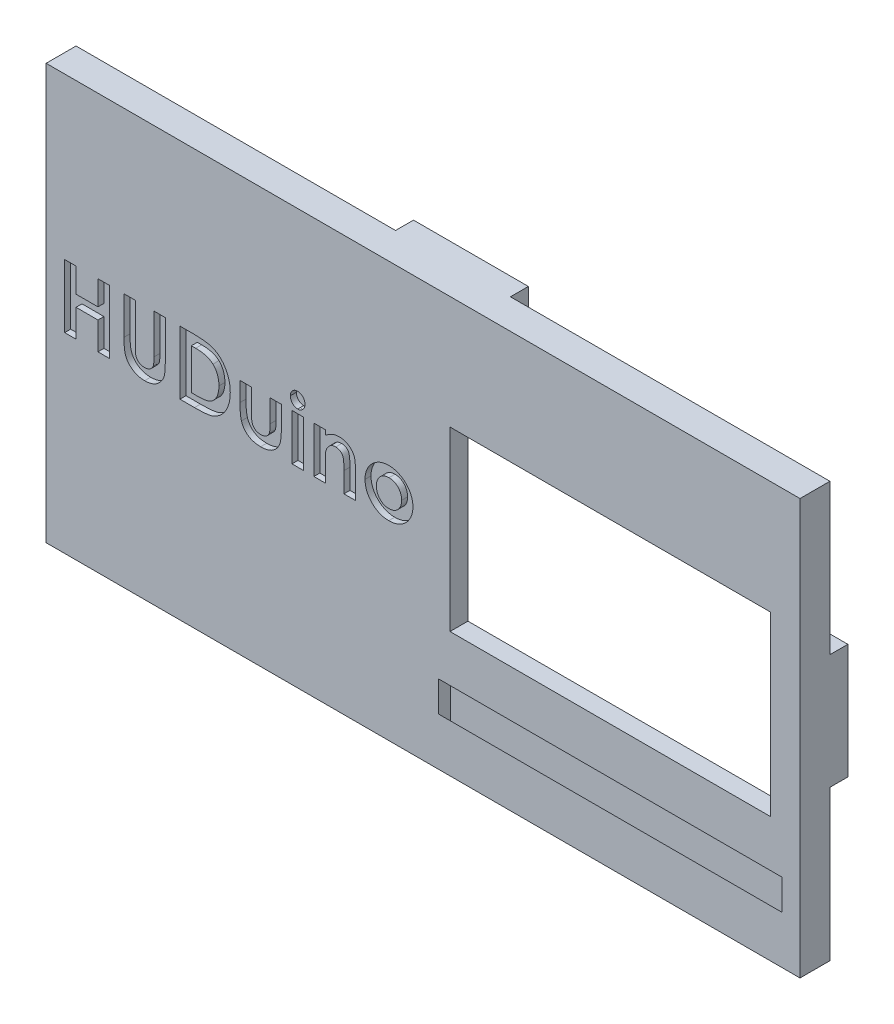
SolidWorks part; units mm, degrees
ref_plane "Alzado" through (0, 0, 0) normal (0, 0, 1) x (1, 0, 0)
ref_plane "Planta" through (0, 0, 0) normal (0, 1, 0) x (1, 0, 0)
ref_plane "Vista lateral" through (0, 0, 0) normal (1, 0, 0) x (0, 0, -1)
sketch "Croquis1" plane through (0, 0, 0) normal (0, 0, 1) x (1, 0, 0)
  line L1 (-29.7943, 14.4088) -> (33.2057, 14.4088)
  line L2 (-29.7943, 14.4088) -> (-29.7943, -20.2912)
  line L3 (-29.7943, -20.2912) -> (33.2057, -20.2912)
  line L4 (33.2057, 14.4088) -> (33.2057, -20.2912)
  dimension "D1" = 63
  dimension "D2" = 34.7
extrude "Saliente-Extruir1" add sketch "Croquis1" along normal blind 1.5
sketch "Croquis3" plane through (0, 0, 0) normal (0, 0, -1) x (-1, 0, 0)
  line L1 (-33.2057, 14.4088) -> (29.7943, 14.4088)
  line L2 (-33.2057, 14.4088) -> (-33.2057, -20.2912)
  line L3 (-33.2057, -20.2912) -> (29.7943, -20.2912)
  line L4 (29.7943, 14.4088) -> (29.7943, -20.2912)
  line L5 (-31.7057, 12.9088) -> (28.2943, 12.9088)
  line L6 (-31.7057, 12.9088) -> (-31.7057, -18.7912)
  line L7 (-31.7057, -18.7912) -> (28.2943, -18.7912)
  line L8 (28.2943, 12.9088) -> (28.2943, -18.7912)
  dimension "D1" = 1.5
  dimension "D2" = 1.5
  dimension "D3" = 1.5
  dimension "D4" = 1.5
extrude "Saliente-Extruir2" add sketch "Croquis3" along normal blind 1
sketch "Croquis4" plane through (0, 0, -1) normal (0, 0, -1) x (-1, 0, 0)
  line L0 (29.7943, 14.4088) -> (-33.2057, 14.4088) construction
  line L1 (-6.5057, 14.4088) -> (3.0943, 14.4088)
  line L2 (-6.5057, 14.4088) -> (-6.5057, 12.9088)
  line L3 (-6.5057, 12.9088) -> (3.0943, 12.9088)
  line L4 (3.0943, 14.4088) -> (3.0943, 12.9088)
  line L5 (28.2943, 12.9088) -> (-31.7057, 12.9088) construction
  line L6 (-33.2057, 14.4088) -> (-33.2057, -20.2912) construction
  line L7 (-33.2057, 1.8588) -> (-31.7057, 1.8588)
  line L8 (-33.2057, 1.8588) -> (-33.2057, -7.7412)
  line L9 (-33.2057, -7.7412) -> (-31.7057, -7.7412)
  line L10 (-31.7057, 1.8588) -> (-31.7057, -7.7412)
  line L11 (-31.7057, 12.9088) -> (-31.7057, -18.7912) construction
  line L17 (29.7943, -20.2912) -> (29.7943, 14.4088) construction
  line L18 (-31.7057, -18.7912) -> (28.2943, -18.7912) construction
  line L19 (3.0943, -18.7912) -> (-6.5057, -18.7912)
  line L20 (3.0943, -18.7912) -> (3.0943, -20.2912)
  line L21 (3.0943, -20.2912) -> (-6.5057, -20.2912)
  line L22 (-6.5057, -18.7912) -> (-6.5057, -20.2912)
  line L23 (-33.2057, -20.2912) -> (29.7943, -20.2912) construction
  line L24 (28.2943, -18.7912) -> (28.2943, 12.9088) construction
  line L25 (28.2943, 1.8588) -> (29.7943, 1.8588)
  line L26 (28.2943, 1.8588) -> (28.2943, -7.7412)
  line L27 (28.2943, -7.7412) -> (29.7943, -7.7412)
  line L28 (29.7943, 1.8588) -> (29.7943, -7.7412)
  point P32 (-1.7057, 14.4088)
  point P33 (-33.2057, -2.9412)
  dimension "D1" = 9.6
  dimension "D3" = 9.6
  dimension "D4" = 9.6
  dimension "D5" = 31.5
  dimension "D6" = 17.35
extrude "Saliente-Extruir3" add sketch "Croquis4" along normal blind 1.5
sketch "Croquis6" plane through (0, 0, 1.5) normal (0, 0, 1) x (1, 0, 0)
  line L0 (33.2057, -20.2912) -> (33.2057, 14.4088) construction
  line L1 (3.9557, 4.9588) -> (30.7557, 4.9588)
  line L2 (3.9557, 4.9588) -> (3.9557, -9.8412)
  line L3 (3.9557, -9.8412) -> (30.7557, -9.8412)
  line L4 (30.7557, 4.9588) -> (30.7557, -9.8412)
  line L5 (33.2057, 14.4088) -> (-29.7943, 14.4088) construction
  dimension "D1" = 2.45
  dimension "D2" = 9.45
  dimension "D3" = 26.8
  dimension "D4" = 14.8
extrude "Cortar-Extruir1" cut sketch "Croquis6" against normal blind 21.5
sketch "Croquis8" plane through (33.2057, 0, 0) normal (1, 0, 0) x (0, 0, -1)
  line L0 (0, -15.2457) -> (-2.7106, -12.535)
  line L4 (-1.5, -20.2912) -> (-1.5, 14.4088) construction
  line L5 (0, -17.7912) -> (-2.8682, -14.923)
  line L6 (-2.7106, -12.535) -> (-2.8682, -14.923)
  line L7 (0, -17.7912) -> (0, -15.2457)
  dimension "D1" = 45
  dimension "D2" = 1.8
extrude "Cortar-Extruir2" cut sketch "Croquis8" against normal blind 32
sketch "Croquis9" plane through (0, 0, 1.5) normal (0, 0, 1) x (1, 0, 0)
  line L0 (33.2057, -20.2912) -> (33.2057, -16.2912) construction
  line L1 (-1.5556, -11.4775) -> (3.0057, -11.4775)
  line L2 (-1.5556, -11.4775) -> (-1.5556, -19.1016)
  line L3 (-1.5556, -19.1016) -> (3.0057, -19.1016)
  line L4 (3.0057, -11.4775) -> (3.0057, -19.1016)
  line L5 (31.7057, -11.4775) -> (33.2057, -11.4775)
  line L6 (31.7057, -11.4775) -> (31.7057, -18.2912)
  line L7 (31.7057, -18.2912) -> (33.2057, -18.2912)
  line L8 (33.2057, -11.4775) -> (33.2057, -18.2912)
  line L10 (3.9557, 4.9588) -> (3.9557, -9.8412) construction
  dimension "D1" = 1.5
  dimension "D2" = 0.95
extrude "Saliente-Extruir4" add sketch "Croquis9" against normal up to surface (1.5 mm away) up to face at (9.0807, -9.7298, 0)
sketch "Croquis10" plane through (0, 0, 0) normal (0, 0, -1) x (-1, 0, 0)
  line L5 (-3.0057, -17.7912) -> (-31.7057, -17.7912)
  line L6 (-3.0057, -17.7912) -> (-3.0057, -11.2169)
  line L7 (-3.0057, -11.2169) -> (-31.7057, -11.2169)
  line L8 (-31.7057, -17.7912) -> (-31.7057, -11.2169)
extrude "Saliente-Extruir5" add sketch "Croquis10" against normal blind 0.5
sketch "Croquis12" plane through (0, 0, 1.5) normal (0, 0, 1) x (1, 0, 0)
  text T0 "HUDuino" font "Century Gothic" height in points 20
extrude "Cortar-Extruir3" cut sketch "Croquis12" against normal blind 0.5
